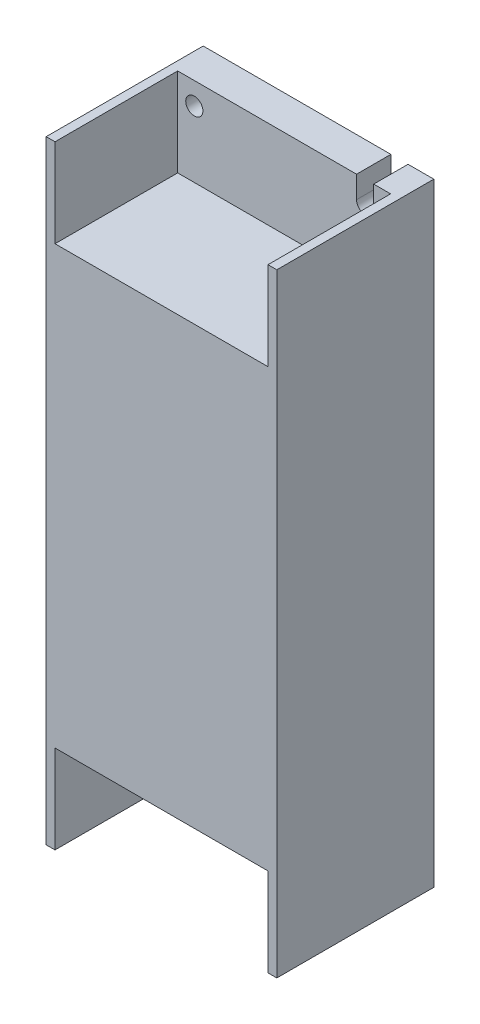
SolidWorks part; units mm, degrees
ref_plane "前视基准面" through (0, 0, 0) normal (0, 0, 1) x (1, 0, 0)
ref_plane "上视基准面" through (0, 0, 0) normal (0, 1, 0) x (1, 0, 0)
ref_plane "右视基准面" through (0, 0, 0) normal (1, 0, 0) x (0, 0, -1)
sketch "草图1" plane through (0, 0, 0) normal (0, 0, 1) x (1, 0, 0)
  line L1 (-23.5, 62.5) -> (23.5, 62.5)
  line L2 (-23.5, 62.5) -> (-23.5, -62.5)
  line L3 (-23.5, -62.5) -> (23.5, -62.5)
  line L4 (23.5, 62.5) -> (23.5, -62.5)
  line L5 (-23.5, 62.5) -> (23.5, -62.5) construction
  line L6 (-23.5, -62.5) -> (23.5, 62.5) construction
  point P0 (0, 0)
  dimension "D1" = 47
  dimension "D2" = 125
extrude "凸台-拉伸1" add sketch "草图1" along normal blind 32
sketch "草图2" plane through (0, 0, 32) normal (0, 0, 1) x (1, 0, 0)
  line L0 (23.5, -62.5) -> (23.5, 62.5) construction
  line L2 (23.5, 62.5) -> (-23.5, 62.5) construction
  line L3 (-21.7, 62.5) -> (21.7, 62.5)
  line L4 (-21.7, 62.5) -> (-21.7, 44.5)
  line L5 (-21.7, 44.5) -> (21.7, 44.5)
  line L6 (21.7, 62.5) -> (21.7, 44.5)
  line L8 (-23.5, 62.5) -> (-23.5, -62.5) construction
  dimension "D1" = 1.8
  dimension "D2" = 18
  dimension "D3" = 1.8
extrude "切除-拉伸1" cut sketch "草图2" against normal offset from surface (25 mm away) 7 up to face at (0, 0, 0)
sketch "草图4" plane through (0, 0, 0) normal (0, 0, -1) x (-1, 0, 0)
  line L0 (14.75, -58) -> (14.75, -62.5)
  line L1 (18.3126, 58) -> (-16.5, 58) construction
  line L2 (-48.0648, 0) -> (44.0202, 0) construction
  line L3 (0, 80.4418) -> (0, -76.2597) construction
  line L4 (14.75, -62.5) -> (18.25, -62.5)
  line L5 (21.7, 62.5) -> (-21.7, 62.5) construction
  line L6 (18.25, -62.5) -> (18.25, -58)
  line L7 (-14.75, 58) -> (-14.75, 62.5)
  line L8 (-14.75, 62.5) -> (-18.25, 62.5)
  line L9 (-18.25, 62.5) -> (-18.25, 58)
  line L10 (-18.3126, -58) -> (16.5, -58) construction
  line L11 (48.0648, 0) -> (-44.0202, 0) construction
  circle A0 centre (-18.3126, -58) radius 1.75
  circle A1 centre (18.3126, 58) radius 1.75
  arc A2 (14.75, -58) -> (18.25, -58) centre (16.5, -58) cw
  arc A4 (-14.75, 58) -> (-18.25, 58) centre (-16.5, 58) cw
  point P0 (0, 0)
  point P27 (0, 0)
  dimension "D5" = 3.5
  dimension "D6" = 1.75
  dimension "D1" = 2
  dimension "D4" = 4.5
extrude "切除-拉伸2" cut sketch "草图4" against normal blind 10
mirror "镜向1" about plane through (0, 0, 0) normal (0, 1, 0) of "切除-拉伸1"
